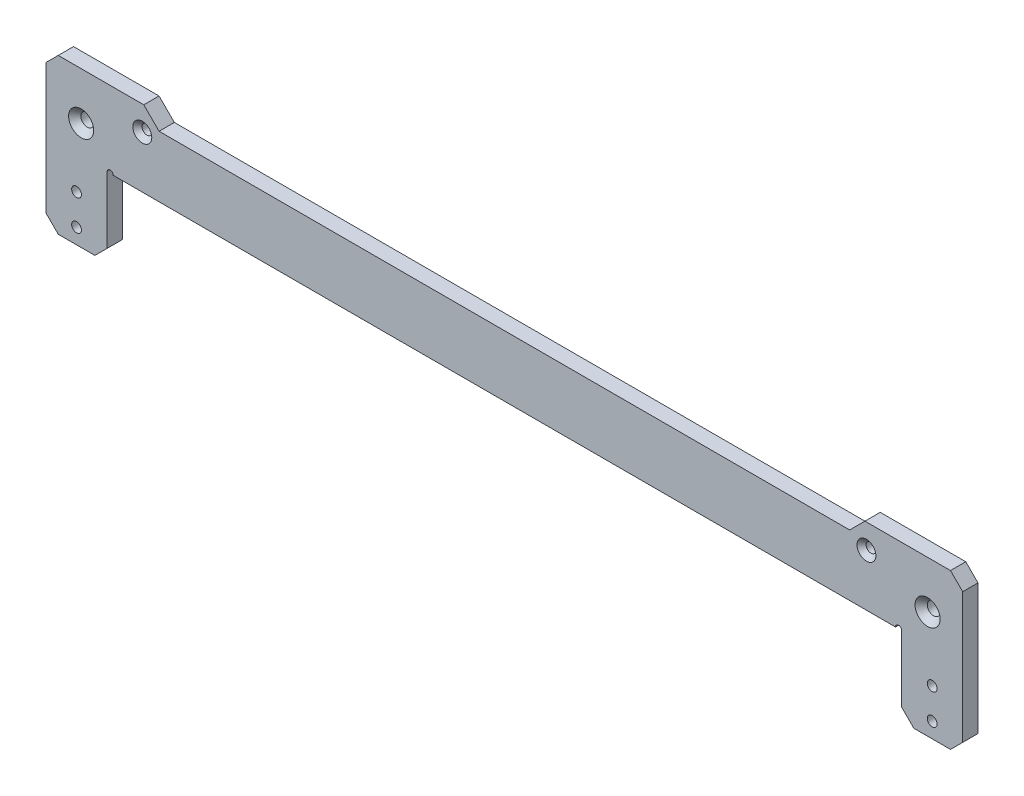
SolidWorks part; units mm, degrees
ref_plane "前视基准面" through (0, 0, 0) normal (0, 0, 1) x (1, 0, 0)
ref_plane "上视基准面" through (0, 0, 0) normal (0, 1, 0) x (1, 0, 0)
ref_plane "右视基准面" through (0, 0, 0) normal (1, 0, 0) x (0, 0, -1)
sketch "草图1" plane through (0, 0, 0) normal (0, 0, 1) x (1, 0, 0)
  line L0 (-150, 40.7) -> (-150, -10)
  line L1 (140, -5) -> (-140, -5) construction
  line L2 (140, -5) -> (140, 5) construction
  line L3 (140, 5) -> (-140, 5) construction
  line L4 (-140, -5) -> (-140, 5) construction
  line L5 (140, -5) -> (-140, 5) construction
  line L6 (140, 5) -> (-140, -5) construction
  line L7 (-150, -10) -> (-130, -10)
  line L8 (-130, -10) -> (-130, 15.7)
  line L9 (-130, 15.7) -> (130, 15.7)
  line L10 (130, 15.7) -> (130, -10)
  line L11 (130, -10) -> (150, -10)
  line L12 (150, -10) -> (150, 40.7)
  line L13 (150, 40.7) -> (-150, 40.7)
  circle A0 centre (-140, 5) radius 1.6
  circle A1 centre (-140, -5) radius 1.6
  circle A2 centre (140, 5) radius 1.6
  circle A3 centre (140, -5) radius 1.6
  point P0 (0, 0)
  point P10 (140, -10)
  dimension "D3" = 3.2
  dimension "D1" = 280
  dimension "D2" = 10
  dimension "D4" = 10
  dimension "D5" = 10
  dimension "D6" = 5
  dimension "D7" = 20.7
  dimension "D8" = 25
extrude "凸台-拉伸1" add sketch "草图1" along normal mid plane 5
sketch "草图4" plane through (0, 0, 2.5) normal (0, 0, 1) x (1, 0, 0)
  line L0 (118, 40.7) -> (113, 35.7)
  line L1 (150, 40.7) -> (-150, 40.7) construction
  line L2 (113, 35.7) -> (-113, 35.7)
  line L3 (-113, 35.7) -> (-118, 40.7)
  line L4 (-118, 40.7) -> (118, 40.7)
  line L5 (150, -10) -> (150, 40.7) construction
  point P6 (0, 40.7)
  dimension "D1" = 5
  dimension "D2" = 45
  dimension "D3" = 32
extrude "切除-拉伸2" cut sketch "草图4" against normal through all
chamfer "倒角2" distance 4 angle 45 6 edges at (-150, 40.7, 0) (-150, -10, 0) (-130, -10, 0) (130, -10, 0) (150, -10, 0) (150, 40.7, 0)
sketch "草图6" plane through (0, 0, -2.5) normal (0, 0, -1) x (-1, 0, 0)
  line L0 (130, 15.7) -> (-130, 15.7) construction
  circle A0 centre (129, 15.7) radius 1
  circle A1 centre (-129, 15.7) radius 1
  dimension "D1" = 2
extrude "切除-拉伸3" cut sketch "草图6" against normal through all
sketch "草图7" plane through (0, 0, 2.5) normal (0, 0, 1) x (1, 0, 0)
  line L0 (-150, 36.7) -> (-150, -6) construction
  line L1 (-118, 40.7) -> (-146, 40.7) construction
  line L2 (118.4853, 32.7) -> (-118.4853, 32.7) construction
  line L6 (146, 40.7) -> (118, 40.7) construction
  line L7 (113, 35.7) -> (118, 40.7) construction
  line L8 (0, 32.7) -> (0, 15.7) construction
  line L9 (-128, 15.7) -> (128, 15.7) construction
  circle A0 centre (-138.5, 25.2) radius 2.1
  circle A1 centre (-118.4853, 32.7) radius 2.5 construction
  circle A2 centre (118.4853, 32.7) radius 2.5 construction
  circle A3 centre (118.4853, 32.7) radius 1.6
  circle A4 centre (-118.4853, 32.7) radius 1.6
  circle A5 centre (138.5, 25.2) radius 2.1
  point P16 (0, 32.7)
  dimension "D1" = 4.2
  dimension "D2" = 11.5
  dimension "D3" = 5
  dimension "D4" = 3.2
  dimension "D5" = 8
  dimension "D6" = 6
  dimension "D7" = 15.5
extrude "切除-拉伸4" cut sketch "草图7" against normal through all
chamfer "倒角3" distance 1.5 angle 45 2 edges at (120.0853, 32.7, 2.5) (-116.8853, 32.7, 2.5)
chamfer "倒角4" distance 2 angle 45 2 edges at (-136.4, 25.2, 2.5) (136.4, 25.2, 2.5)
equation "\"D5@草图1\"=\"D4@草图1\""
